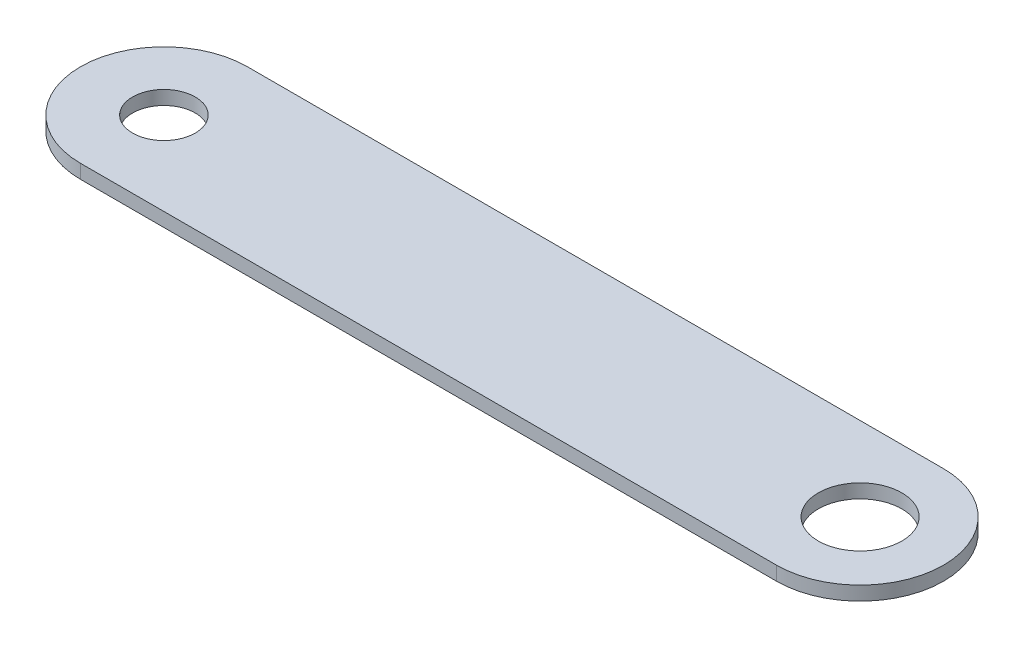
SolidWorks part; units mm, degrees
material "1060 Alloy"
ref_plane "Front Plane" through (0, 0, 0) normal (0, 0, 1) x (1, 0, 0)
ref_plane "Top Plane" through (0, 0, 0) normal (0, 1, 0) x (1, 0, 0)
ref_plane "Right Plane" through (0, 0, 0) normal (1, 0, 0) x (0, 0, -1)
sketch "Sketch1" plane through (0, 0, 0) normal (0, 1, 0) x (1, 0, 0)
  line L0 (0, 0) -> (50, 0) construction
  line L1 (0, 6) -> (50, 6)
  line L2 (0, -6) -> (50, -6)
  arc A0 (0, 6) -> (0, -6) centre (0, 0) ccw
  arc A1 (50, -6) -> (50, 6) centre (50, 0) ccw
  circle A2 centre (0, 0) radius 2.25
  circle A3 centre (50, 0) radius 3
  point P3 (25, 0)
  dimension "D3" = 4.5
  dimension "D4" = 6
  dimension "D1" = 50
  dimension "D2" = 12
extrude "Boss-Extrude1" add sketch "Sketch1" along normal blind 1
